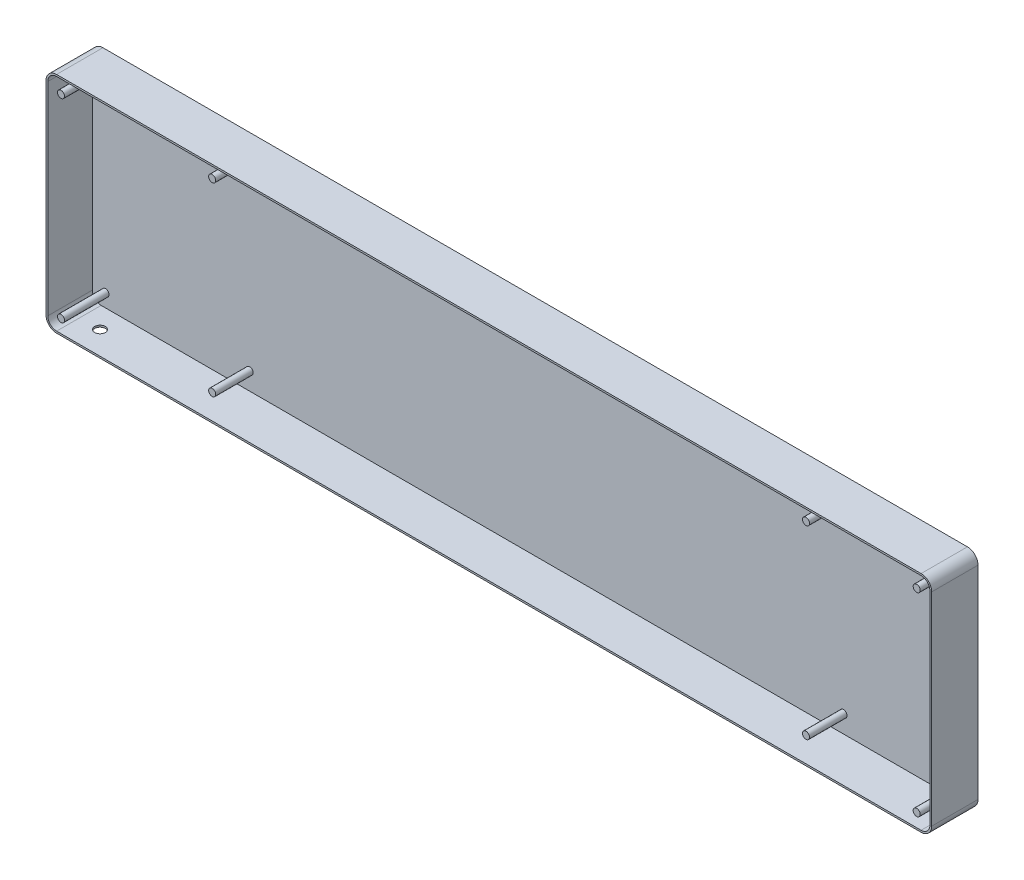
SolidWorks part; units mm, degrees
ref_plane "Plan de face" through (0, 0, 0) normal (0, 0, 1) x (1, 0, 0)
ref_plane "Plan de dessus" through (0, 0, 0) normal (0, 1, 0) x (1, 0, 0)
ref_plane "Plan de droite" through (0, 0, 0) normal (1, 0, 0) x (0, 0, -1)
sketch "Esquisse2" plane through (0, 0, 0) normal (0, 0, 1) x (1, 0, 0)
  line L4 (-295.2211, 123.5372) -> (-295.2211, -106.4628)
  line L5 (-285.2211, -116.4628) -> (694.7789, -116.4628)
  line L6 (704.7789, -106.4628) -> (704.7789, 123.5372)
  line L7 (694.7789, 133.5372) -> (-285.2211, 133.5372)
  line L8 (694.7789, 135.5372) -> (-285.2211, 135.5372)
  line L9 (-297.2211, 123.5372) -> (-297.2211, -106.4628)
  line L10 (-285.2211, -118.4628) -> (694.7789, -118.4628)
  line L11 (706.7789, -106.4628) -> (706.7789, 123.5372)
  arc A4 (-295.2211, -106.4628) -> (-285.2211, -116.4628) centre (-285.2211, -106.4628) ccw
  arc A5 (694.7789, -116.4628) -> (704.7789, -106.4628) centre (694.7789, -106.4628) ccw
  arc A6 (704.7789, 123.5372) -> (694.7789, 133.5372) centre (694.7789, 123.5372) ccw
  arc A7 (-285.2211, 133.5372) -> (-295.2211, 123.5372) centre (-285.2211, 123.5372) ccw
  arc A8 (-285.2211, 135.5372) -> (-297.2211, 123.5372) centre (-285.2211, 123.5372) ccw
  arc A9 (-297.2211, -106.4628) -> (-285.2211, -118.4628) centre (-285.2211, -106.4628) ccw
  arc A10 (694.7789, -118.4628) -> (706.7789, -106.4628) centre (694.7789, -106.4628) ccw
  arc A11 (706.7789, 123.5372) -> (694.7789, 135.5372) centre (694.7789, 123.5372) ccw
  dimension "D1" = 2
extrude "Boss.-Extru.1" add sketch "Esquisse2" against normal blind 50.5
sketch "Esquisse4" plane through (0, 0, -50.5) normal (0, 0, -1) x (-1, 0, 0)
  line L0 (297.2211, 123.5372) -> (297.2211, -106.4628) construction
  line L1 (285.2211, -118.4628) -> (-694.7789, -118.4628) construction
  line L2 (-706.7789, -106.4628) -> (-706.7789, 123.5372) construction
  line L3 (-694.7789, 135.5372) -> (285.2211, 135.5372) construction
  line L4 (297.2211, 123.5372) -> (297.2211, -106.4628)
  line L5 (285.2211, -118.4628) -> (-694.7789, -118.4628)
  line L6 (-706.7789, -106.4628) -> (-706.7789, 123.5372)
  line L7 (-694.7789, 135.5372) -> (285.2211, 135.5372)
  arc A0 (285.2211, -118.4628) -> (297.2211, -106.4628) centre (285.2211, -106.4628) ccw construction
  arc A1 (297.2211, 123.5372) -> (285.2211, 135.5372) centre (285.2211, 123.5372) ccw construction
  arc A2 (-706.7789, -106.4628) -> (-694.7789, -118.4628) centre (-694.7789, -106.4628) ccw construction
  arc A3 (-694.7789, 135.5372) -> (-706.7789, 123.5372) centre (-694.7789, 123.5372) ccw construction
  arc A4 (285.2211, -118.4628) -> (297.2211, -106.4628) centre (285.2211, -106.4628) ccw
  arc A5 (297.2211, 123.5372) -> (285.2211, 135.5372) centre (285.2211, 123.5372) ccw
  arc A6 (-706.7789, -106.4628) -> (-694.7789, -118.4628) centre (-694.7789, -106.4628) ccw
  arc A7 (-694.7789, 135.5372) -> (-706.7789, 123.5372) centre (-694.7789, 123.5372) ccw
extrude "Boss.-Extru.2" add sketch "Esquisse4" along normal blind 2
sketch "Esquisse6" plane through (0, 0, -50.5) normal (0, 0, 1) x (1, 0, 0)
  line L0 (694.7789, 133.5372) -> (-285.2211, 133.5372) construction
  line L1 (-295.2211, 123.5372) -> (-295.2211, -106.4628) construction
  line L2 (-295.2211, 8.5372) -> (704.7789, 8.5372) construction
  line L3 (704.7789, -106.4628) -> (704.7789, 123.5372) construction
  line L4 (204.7789, 133.5372) -> (204.7789, -116.4628) construction
  line L5 (-285.2211, -116.4628) -> (694.7789, -116.4628) construction
  circle A0 centre (-280.2211, 118.5372) radius 4
  circle A1 centre (-280.2211, -101.4628) radius 4
  circle A2 centre (689.7789, -101.4628) radius 4
  circle A3 centre (689.7789, 118.5372) radius 4
  dimension "D1" = 15
  dimension "D2" = 15
extrude "Boss.-Extru.4" add sketch "Esquisse6" along normal up to surface (50.5 mm away) up to face at (204.7789, 8.5372, 0)
sketch "Esquisse7" plane through (0, 0, -50.5) normal (0, 0, 1) x (1, 0, 0)
  circle A0 centre (-116.8425, 113.5372) radius 4
  circle A1 centre (-116.8425, -96.4628) radius 4
  circle A2 centre (556.2895, 113.5372) radius 4
  circle A3 centre (556.2895, -96.4628) radius 4
extrude "Boss.-Extru.5" add sketch "Esquisse7" along normal blind 42.5
sketch "Esquisse8" plane through (0, -118.4628, 0) normal (0, -1, 0) x (-1, 0, 0)
  line L1 (285.2211, 26.25) -> (226.4055, 26.25) construction
  line L2 (285.2211, 52.5) -> (285.2211, 0) construction
  line L3 (297.2211, 52.5) -> (297.2211, 0) construction
  circle A0 centre (262.2211, 26.25) radius 6
  point P2 (259.4053, 26.25)
  point P8 (259.0409, 27.7677)
  dimension "D1" = 12
  dimension "D2" = 35
extrude "Enlèv. mat.-Extru.1" cut sketch "Esquisse8" against normal blind 2
